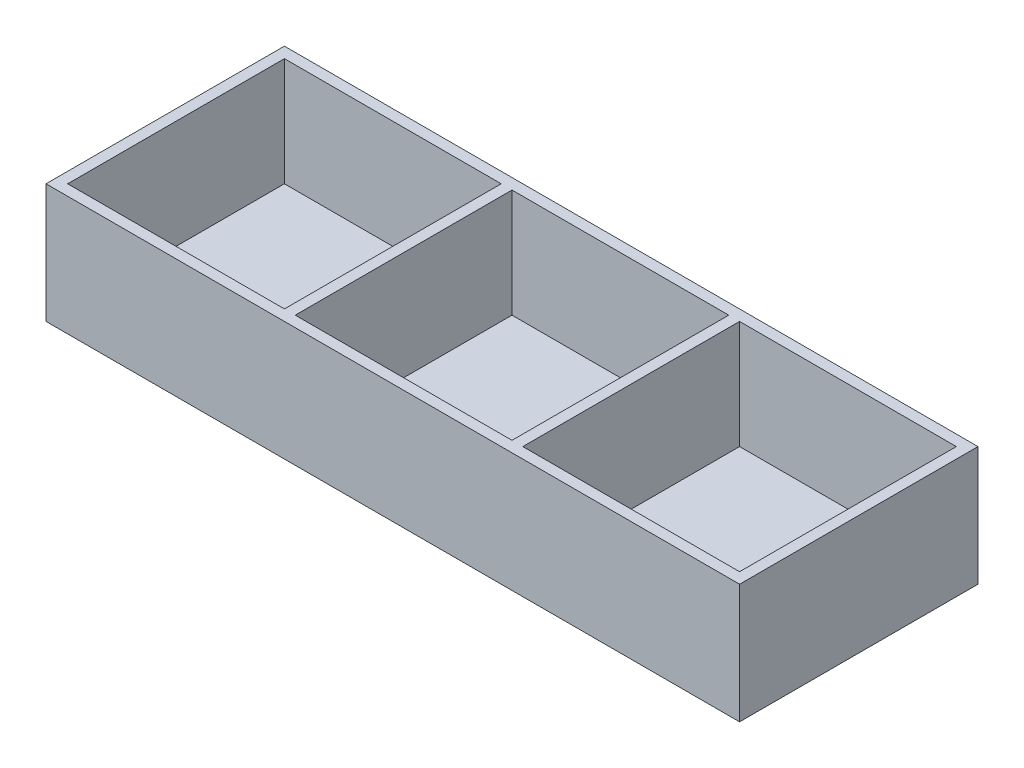
SolidWorks part; units mm, degrees
ref_plane "前视基准面" through (0, 0, 0) normal (0, 0, 1) x (1, 0, 0)
ref_plane "上视基准面" through (0, 0, 0) normal (0, 1, 0) x (1, 0, 0)
ref_plane "右视基准面" through (0, 0, 0) normal (1, 0, 0) x (0, 0, -1)
sketch "草图1" plane through (0, 0, 0) normal (0, 1, 0) x (1, 0, 0)
  line L1 (-160, -55) -> (160, -55)
  line L2 (-160, -55) -> (-160, 55)
  line L3 (-160, 55) -> (160, 55)
  line L4 (160, -55) -> (160, 55)
  line L5 (-160, -55) -> (160, 55) construction
  line L6 (-160, 55) -> (160, -55) construction
  point P0 (0, 0)
extrude "凸台-拉伸1" add sketch "草图1" along normal blind 55
shell "抽壳1" thickness 5
sketch "草图2" plane through (0, 55, 0) normal (0, 1, 0) x (1, 0, 0)
  line L0 (52.5, 50) -> (52.5, -50)
  line L1 (155, 50) -> (-155, 50) construction
  line L2 (-52.5, 50) -> (-52.5, -50)
  line L3 (-155, -50) -> (155, -50) construction
rib "筋1" sketch "草图2" sketch "草图2" thickness 5 extrusion direction normal to sketch draft on no parameters "D1"=5
